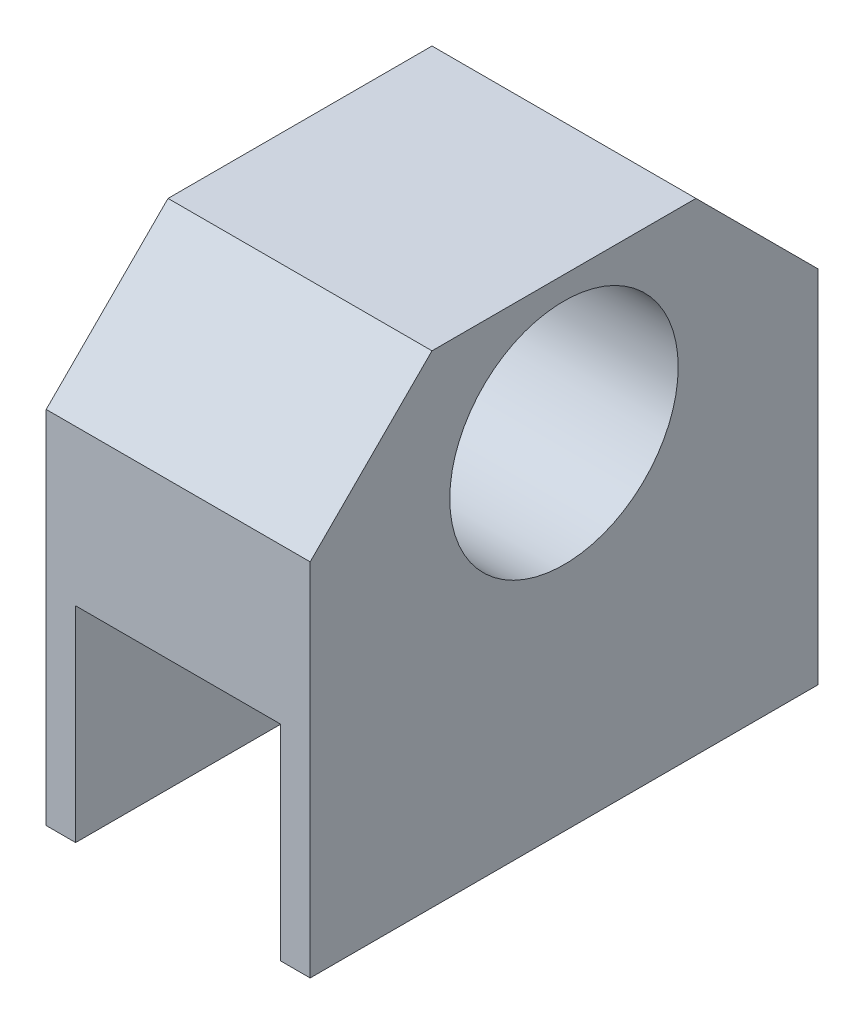
SolidWorks part; units mm, degrees
ref_plane "Спереди" through (0, 0, 0) normal (0, 0, 1) x (1, 0, 0)
ref_plane "Сверху" through (0, 0, 0) normal (0, 1, 0) x (1, 0, 0)
ref_plane "Справа" through (0, 0, 0) normal (1, 0, 0) x (0, 0, -1)
other "Configuration Table"
sketch "Эскиз1" plane through (0, 0, 0) normal (1, 0, 0) x (0, 0, -1)
  line L0 (0, 0) -> (0, 25) construction
  line L1 (-25, 25) -> (25, 25) construction
  line L2 (-25, 25) -> (-25, 22.5) construction
  line L3 (-25, -25) -> (25, -25)
  line L4 (25, 25) -> (25, 22.5) construction
  line L5 (-25, 25) -> (25, -25) construction
  line L6 (-25, -25) -> (25, 25) construction
  line L7 (0, 25) -> (0, 59.7055) construction
  line L8 (-13, 22.5) -> (13, 22.5)
  line L9 (-25, 10.5) -> (-13, 22.5)
  line L10 (25, 10.5) -> (13, 22.5)
  line L11 (-25, 22.5) -> (-22.5, 22.5) construction
  line L12 (-22.5, 22.5) -> (-13, 22.5) construction
  line L13 (22.5, 22.5) -> (25, 22.5) construction
  line L14 (13, 22.5) -> (22.5, 22.5) construction
  line L15 (-25, 22.5) -> (-25, 10.5) construction
  line L16 (-25, 10.5) -> (-25, -25)
  line L17 (25, 22.5) -> (25, 10.5) construction
  line L18 (25, 10.5) -> (25, -25)
  circle A0 centre (0, 9) radius 11.25
  point P0 (0, 0)
  point P15 (-25, -1.4432)
  point P18 (-25, 2.2218)
  point P19 (25, 1.2537)
  point P22 (-13, 14.5999)
  point P23 (0, 0)
  dimension "D1" = 22.5
  dimension "D2" = 9
  dimension "D3" = 25
  dimension "D4" = 50
  dimension "D5" = 45
  dimension "D6" = 13.5
  dimension "D7" = 12
extrude "Бобышка-Вытянуть1" add sketch "Эскиз1" along normal mid plane 26
sketch "Эскиз2" plane through (0, 0, -25) normal (0, 0, -1) x (-1, 0, 0)
  line L0 (0, 0) -> (0, -25) construction
  line L2 (-10.1, -25) -> (10.1, -25)
  line L3 (-10.1, -25) -> (-10.1, -4.8)
  line L4 (13, -25) -> (13, 10.5)
  line L5 (13, 10.5) -> (-13, 10.5)
  line L6 (-13, 10.5) -> (-13, -25)
  line L7 (-13, -25) -> (13, -25)
  line L8 (13, -25) -> (13, 10.5) construction
  line L9 (13, 10.5) -> (-13, 10.5) construction
  line L10 (-13, 10.5) -> (-13, -25) construction
  line L11 (-13, -25) -> (13, -25) construction
  line L12 (-10.1, -4.8) -> (10.1, -4.8)
  line L13 (10.1, -25) -> (10.1, -4.8)
  line L14 (-10.1, -25) -> (10.1, -4.8) construction
  line L15 (-10.1, -4.8) -> (10.1, -25) construction
  point P6 (0, -14.9)
  point P7 (0, -14.9)
  point P13 (9.9947, -25)
  dimension "D2" = 10.1
  dimension "D1" = 0
extrude "Вырез-Вытянуть1" cut sketch "Эскиз2" against normal through all
equation "\"RHoleFor8\"= 4.25мм"
equation "\"DHoleFor8\"= 8.5мм"
equation "\"DBearing\"= 22.5мм"
